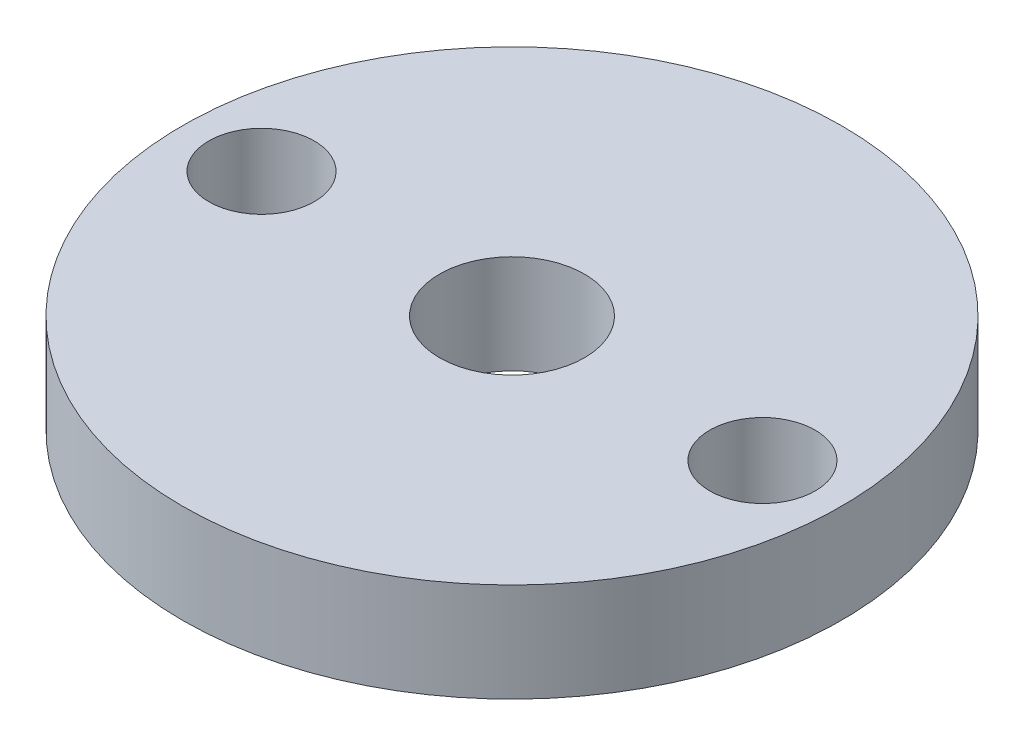
SolidWorks part; units mm, degrees
ref_plane "Front Plane" through (0, 0, 0) normal (0, 0, 1) x (1, 0, 0)
ref_plane "Top Plane" through (0, 0, 0) normal (0, 1, 0) x (1, 0, 0)
ref_plane "Right Plane" through (0, 0, 0) normal (1, 0, 0) x (0, 0, -1)
sketch "Sketch1" plane through (0, 0, 0) normal (0, 1, 0) x (1, 0, 0)
  line L1 (-29, -29) -> (29, -29) construction
  line L2 (-29, -29) -> (-29, 29) construction
  line L3 (-29, 29) -> (29, 29) construction
  line L4 (29, -29) -> (29, 29) construction
  line L5 (0, 29) -> (0, -29) construction
  line L6 (-29, 0) -> (29, 0) construction
  circle A0 centre (-19, 0) radius 1.8
  circle A1 centre (19, 0) radius 1.8
  circle A4 centre (0, 0) radius 5.5
  circle A5 centre (0, 0) radius 25
  point P0 (0, 0)
  dimension "D3" = 3.6
  dimension "D5" = 10
  dimension "D6" = 11
  dimension "D2" = 50
  dimension "D1" = 58
extrude "Boss-Extrude1" add sketch "Sketch1" along normal blind 7.5
sketch "Sketch2" plane through (0, 7.5, 0) normal (0, 1, 0) x (1, 0, 0)
  circle A4 centre (-19, 0) radius 4
  circle A5 centre (19, 0) radius 4
  dimension "D1" = 8
  dimension "D2" = 8
extrude "Cut-Extrude1" cut sketch "Sketch2" against normal blind 6
